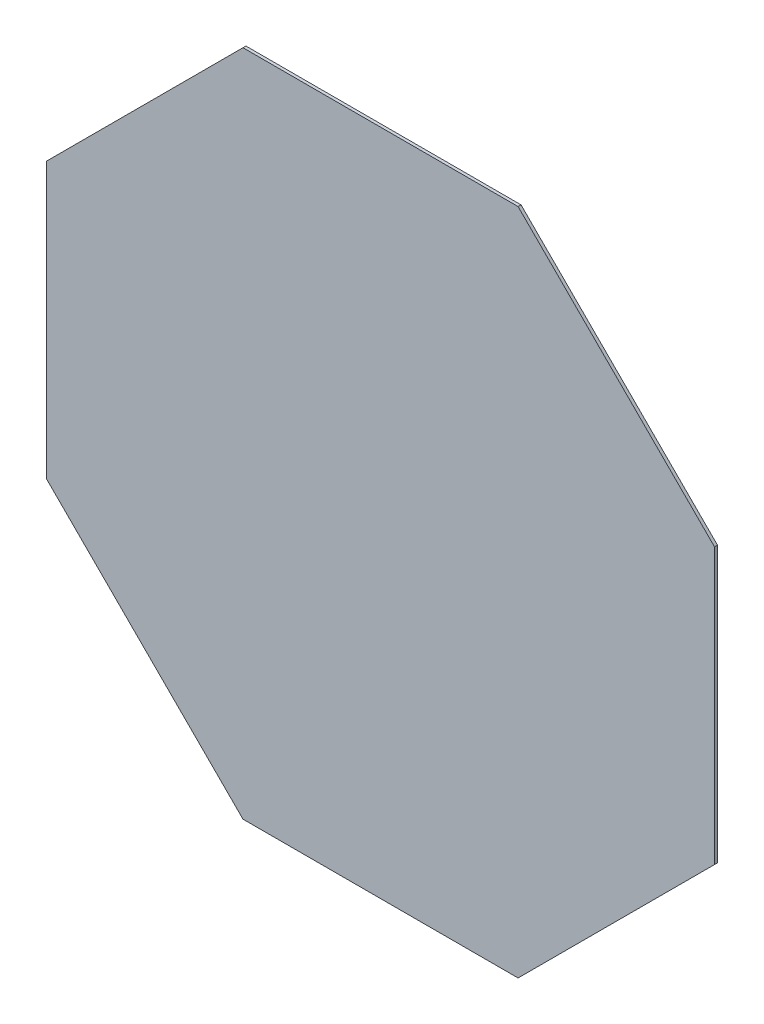
SolidWorks part; units mm, degrees
ref_plane "Plano frontal" through (0, 0, 0) normal (0, 0, 1) x (1, 0, 0)
ref_plane "Plano superior" through (0, 0, 0) normal (0, 1, 0) x (1, 0, 0)
ref_plane "Plano direito" through (0, 0, 0) normal (1, 0, 0) x (0, 0, -1)
sketch "Esboço1" plane through (0, 0, 0) normal (0, 0, 1) x (1, 0, 0)
  line L0 (0, 0) -> (0, 680)
  line L1 (0, 680) -> (680, 680)
  line L2 (680, 680) -> (680, 0)
  line L3 (680, 0) -> (0, 0)
  dimension "D1" = 680
  dimension "D2" = 680
extrude "Ressalto-extrusão1" add sketch "Esboço1" along normal blind 3
chamfer "Chanfro1" distance 200 angle 45 4 edges at (0, 0, 1.5) (680, 0, 1.5) (0, 680, 1.5) (680, 680, 1.5)
